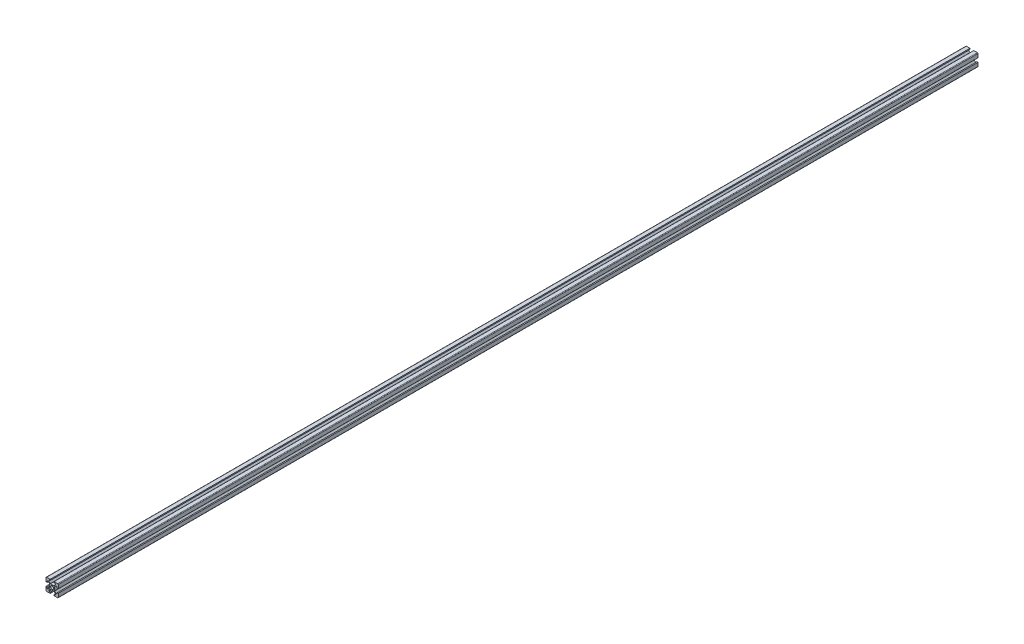
SolidWorks part; units mm, degrees
material "1060 Alloy"
ref_plane "Front Plane" through (0, 0, 0) normal (0, 0, 1) x (1, 0, 0)
ref_plane "Top Plane" through (0, 0, 0) normal (0, 1, 0) x (1, 0, 0)
ref_plane "Right Plane" through (0, 0, 0) normal (1, 0, 0) x (0, 0, -1)
sketch "Sketch1" plane through (0, 0, 0) normal (0, 0, 1) x (1, 0, 0)
  line L0 (20, 0) -> (-8.059, 28.059) construction
  line L1 (0, 0) -> (6.8, 0)
  line L2 (0, 0) -> (0, 6.8)
  line L3 (0, 20) -> (6.8, 20)
  line L4 (20, 0) -> (20, 6.8)
  line L5 (6.8, 20) -> (6.8, 18.2)
  line L6 (20, 20) -> (8.2322, 8.2322) construction
  line L7 (12.95, 6.1) -> (7.05, 6.1)
  line L8 (13.9, 7.05) -> (13.9, 12.95)
  line L9 (12.95, 13.9) -> (7.05, 13.9)
  line L10 (6.1, 7.05) -> (6.1, 12.95)
  line L11 (13.9, 6.1) -> (6.1, 13.9) construction
  line L12 (13.9, 13.9) -> (6.1, 6.1) construction
  line L13 (4.55, 16.4) -> (7.05, 13.9)
  line L14 (13.2, 18.2) -> (13.2, 20)
  line L15 (1.8, 6.8) -> (0, 6.8)
  line L16 (0, 13.2) -> (0, 20)
  line L17 (0, 13.2) -> (1.8, 13.2)
  line L18 (10, 10) -> (10, 13.9) construction
  line L19 (16.4, 4.55) -> (13.9, 7.05)
  line L20 (4.55, 16.4) -> (4.55, 18.2)
  line L21 (4.55, 18.2) -> (6.8, 18.2)
  line L22 (13.2, 18.2) -> (15.45, 18.2)
  line L23 (15.45, 18.2) -> (15.45, 16.4)
  line L24 (15.45, 16.4) -> (12.95, 13.9)
  line L25 (16.4, 4.55) -> (18.2, 4.55)
  line L26 (18.2, 4.55) -> (18.2, 6.8)
  line L27 (20, 6.8) -> (18.2, 6.8)
  line L28 (18.2, 13.2) -> (20, 13.2)
  line L29 (18.2, 13.2) -> (18.2, 15.45)
  line L30 (18.2, 15.45) -> (16.4, 15.45)
  line L31 (16.4, 15.45) -> (13.9, 12.95)
  line L32 (1.8, 4.55) -> (3.6, 4.55)
  line L33 (3.6, 15.45) -> (6.1, 12.95)
  line L34 (3.6, 15.45) -> (1.8, 15.45)
  line L35 (1.8, 15.45) -> (1.8, 13.2)
  line L36 (0, 13.2) -> (1.8, 13.2)
  line L37 (1.8, 6.8) -> (0, 6.8)
  line L38 (3.6, 4.55) -> (6.1, 7.05)
  line L39 (1.8, 6.8) -> (1.8, 4.55)
  line L40 (15.45, 3.6) -> (12.95, 6.1)
  line L41 (4.55, 3.6) -> (7.05, 6.1)
  line L42 (4.55, 1.8) -> (4.55, 3.6)
  line L43 (6.8, 1.8) -> (4.55, 1.8)
  line L44 (6.8, 1.8) -> (6.8, 0)
  line L45 (15.45, 3.6) -> (15.45, 1.8)
  line L46 (15.45, 1.8) -> (13.2, 1.8)
  line L47 (13.2, 0) -> (13.2, 1.8)
  line L48 (13.2, 20) -> (20, 20)
  line L49 (20, 13.2) -> (20, 20)
  line L50 (13.2, 0) -> (20, 0)
  line L51 (6.1, 6.1) -> (-5.5045, -5.5045) construction
  circle A0 centre (10, 10) radius 2.5
  point P25 (10, 16.4)
  point P39 (13.2, 19.1)
  point P46 (0.9, 6.8)
  dimension "D3" = 5
  dimension "D2" = 20
  dimension "D4" = 7.8
  dimension "D5" = 7.8
  dimension "D6" = 6.8
  dimension "D7" = 6.8
  dimension "D8" = 1.8
  dimension "D9" = 10.9
  dimension "D10" = 1.8
  dimension "D11" = 10.9
  dimension "D12" = 20
extrude "Boss-Extrude1" add sketch "Sketch1" along normal blind 1500 contours L47 L50 L4 L27 L26 L25 L19 L8 L31 L30 L29 L28 L49 L48 L14 L22 L23 L24 L9 L13 L20 L21 L5 L3 L16 L17 L35 L34 L33 L10 L38 L32 L39 L15 L2 L1 L44 L43 L42 L41 L7 L40 L45 L46 A0
fillet "Fillet1" radius 1 4 edges at (20, 20, 750) (20, 0, 750) (0, 0, 750) (0, 20, 750)
fillet "Fillet2" radius 0.5 6 edges at (4.55, 18.2, 750) (4.55, 16.4, 750) (7.05, 13.9, 750) (15.45, 18.2, 750) (15.45, 16.4, 750) (12.95, 13.9, 750)
fillet "Fillet3" radius 0.5 6 edges at (18.2, 15.45, 750) (16.4, 15.45, 750) (13.9, 12.95, 750) (18.2, 4.55, 750) (13.9, 7.05, 750) (16.4, 4.55, 750)
fillet "Fillet4" radius 0.5 6 edges at (1.8, 15.45, 750) (3.6, 15.45, 750) (6.1, 12.95, 750) (3.6, 4.55, 750) (1.8, 4.55, 750) (6.1, 7.05, 750)
fillet "Fillet5" radius 0.5 6 edges at (7.05, 6.1, 750) (4.55, 3.6, 750) (4.55, 1.8, 750) (15.45, 1.8, 750) (15.45, 3.6, 750) (12.95, 6.1, 750)
